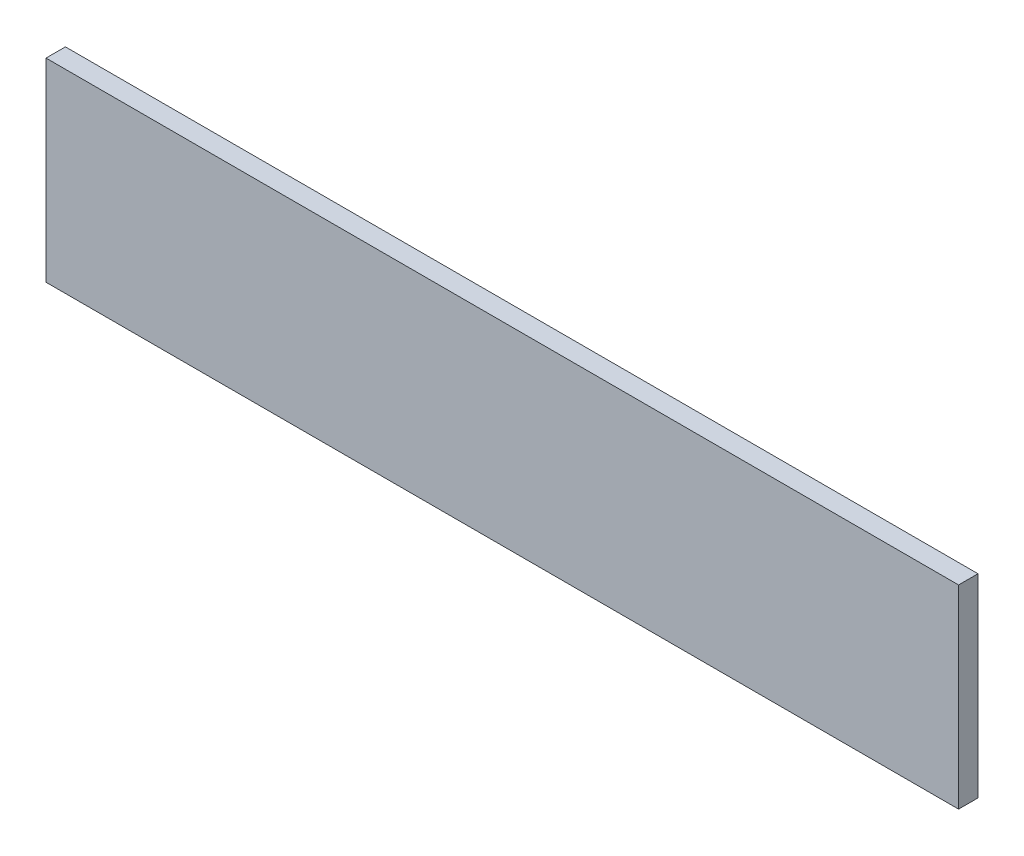
SolidWorks part; units mm, degrees
ref_plane "Front Plane" through (0, 0, 0) normal (0, 0, 1) x (1, 0, 0)
ref_plane "Top Plane" through (0, 0, 0) normal (0, 1, 0) x (1, 0, 0)
ref_plane "Right Plane" through (0, 0, 0) normal (1, 0, 0) x (0, 0, -1)
sketch "Sketch2" plane through (0, 0, 0) normal (0, 0, 1) x (1, 0, 0)
  line L1 (-149.225, -31.75) -> (149.225, -31.75)
  line L2 (-149.225, -31.75) -> (-149.225, 31.75)
  line L3 (-149.225, 31.75) -> (149.225, 31.75)
  line L4 (149.225, -31.75) -> (149.225, 31.75)
  line L5 (-149.225, -31.75) -> (149.225, 31.75) construction
  line L6 (-149.225, 31.75) -> (149.225, -31.75) construction
  point P0 (0, 0)
  dimension "D2" = 63.5
  dimension "D1" = 298.45
extrude "Boss-Extrude1" add sketch "Sketch2" along normal blind 6.35
equation "\"side-panel-width\"= \"converter-cell-inner-length\" + \"bus-bar-cell-inner-length\" + \"material-thickness\""
equation "\"side-panel-height\"= 2.5in"
equation "\"material-thickness\"= 0.25in"
equation "\"converter-cell-inner-length\"= 9in"
equation "\"bus-bar-cell-inner-length\" = 2.5in"
equation "\"D2@Sketch2\"=\"side-panel-height\""
equation "\"D1@Boss-Extrude1\"=\"material-thickness\""
equation "\"D1@Sketch2\"=\"side-panel-width\""
